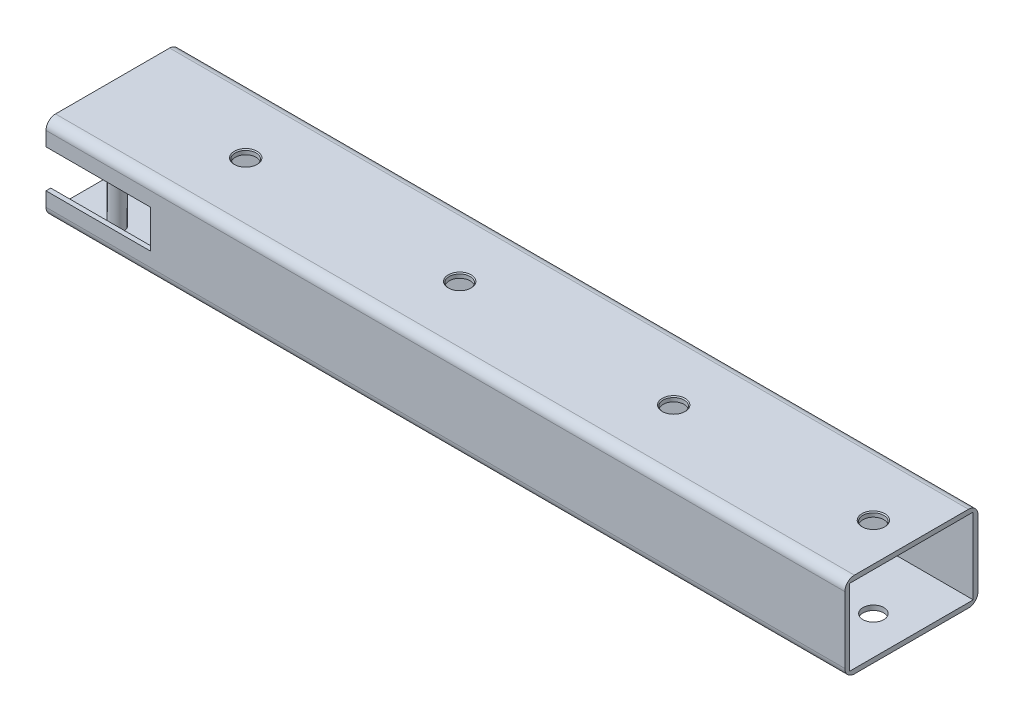
SolidWorks part; units mm, degrees
ref_plane "Front Plane" through (0, 0, 0) normal (0, 0, 1) x (1, 0, 0)
ref_plane "Top Plane" through (0, 0, 0) normal (0, 1, 0) x (1, 0, 0)
ref_plane "Right Plane" through (0, 0, 0) normal (1, 0, 0) x (0, 0, -1)
sketch "Sketch1" plane through (0, 0, 0) normal (0, 1, 0) x (1, 0, 0)
  line L3 (-420, 70) -> (420, 70)
  line L4 (420, -70) -> (420, 70)
  line L5 (-420, -70) -> (420, 70) construction
  line L6 (-420, 70) -> (420, -70) construction
  line L8 (-420, -70) -> (420, -70)
  line L11 (-420, 70) -> (-420, -70)
  point P0 (0, 0)
  dimension "D1" = 840
  dimension "D2" = 140
  dimension "D4" = 140
extrude "Boss-Extrude1" add sketch "Sketch1" along normal blind 90
sketch "Sketch2" plane through (420, 0, 0) normal (1, 0, 0) x (0, 0, -1)
  line L0 (-70, 90) -> (-70, 0) construction
  line L1 (-70, 90) -> (70, 90) construction
  line L2 (-65, 5) -> (65, 5)
  line L3 (70, 90) -> (70, 0) construction
  line L4 (-65, 5) -> (-65, 85)
  line L5 (-65, 85) -> (65, 85)
  line L6 (65, 5) -> (65, 85)
  line L7 (-65, 5) -> (65, 85) construction
  line L8 (-65, 85) -> (65, 5) construction
  point P0 (0, 45)
  point P4 (70, 45)
  dimension "D2" = 5
  dimension "D3" = 5
extrude "Cut-Extrude1" cut sketch "Sketch2" against normal through all contours L2 L6 L5 L4
fillet "Fillet2" radius 10 2 edges at (0, 0, -70) (0, 90, -70)
fillet "Fillet4" radius 10 2 edges at (0, 90, 70) (0, 0, 70)
hole_wizard "M24x2.0 Tapped Hole1" positions "Sketch6" profile "Sketch5" tap size "M24x2.0" standard "ANSI Metric" end condition through all
sketch "Sketch6" plane through (0, 90, 0) normal (0, 1, 0) x (1, 0, 0)
  line L1 (420, -70) -> (-420, -70) construction
  line L2 (-420, 60) -> (-420, -60) construction
  line L3 (420, -60) -> (420, 60) construction
  point P0 (-55, 0)
  point P2 (170, 0)
  point P4 (-280, 0)
  point P15 (380, 0)
  dimension "D1" = 225
  dimension "D2" = 225
  dimension "D3" = 140
  dimension "D4" = 70
  dimension "D5" = 40
sketch "Sketch5" plane through (-55, 90, 0) normal (1, 0, 0) x (0, 0, 1)
  line L0 (0, 0) -> (0, 90)
  line L1 (0, 90) -> (11, 90)
  line L2 (11, 90) -> (11, 1.025)
  line L3 (11, 1.025) -> (12.025, 0)
  line L5 (12.025, 0) -> (0, 0)
  line L6 (-11, 1.025) -> (-12.025, 0) construction
  line L11 (0, -6.35) -> (0, 107.95) construction
  dimension "Thru Tap Drill Dia." = 22
  dimension "Thru Tap Drill Depth" = 90
  dimension "Near C'Sink Dia." = 24.05
  dimension "Near C'Sink Angle" = 90
cosmetic thread "Hole Thread1" parameters "D2"=24
cosmetic thread "Hole Thread2" parameters "D2"=24
cosmetic thread "Hole Thread3" parameters "D2"=24
cosmetic thread "Hole Thread4" parameters "D2"=24
sketch "Sketch7" plane through (0, 0, 70) normal (0, 0, 1) x (1, 0, 0)
  line L0 (-420, 80) -> (-420, 10) construction
  line L1 (-310, 65) -> (-437, 65)
  line L2 (-310, 65) -> (-310, 25)
  line L3 (-310, 25) -> (-437, 25)
  line L4 (-437, 65) -> (-437, 25)
  line L5 (-310, 65) -> (-437, 25) construction
  line L6 (-310, 25) -> (-437, 65) construction
  point P0 (-373.5, 45)
  point P8 (-420, 45)
  dimension "D1" = 40
  dimension "D2" = 127
  dimension "D3" = 17
extrude "Cut-Extrude2" cut sketch "Sketch7" against normal up to next
sketch "Sketch8" plane through (0, 5, 0) normal (0, 1, 0) x (1, 0, 0)
  line L0 (420, -70) -> (-420, -70) construction
  line L3 (-420, 60) -> (-420, -60) construction
  circle A0 centre (-370, -45) radius 7.5
  dimension "D1" = 15
  dimension "D3" = 50
  dimension "D2" = 25
extrude "Boss-Extrude2" add sketch "Sketch8" along normal up to next
